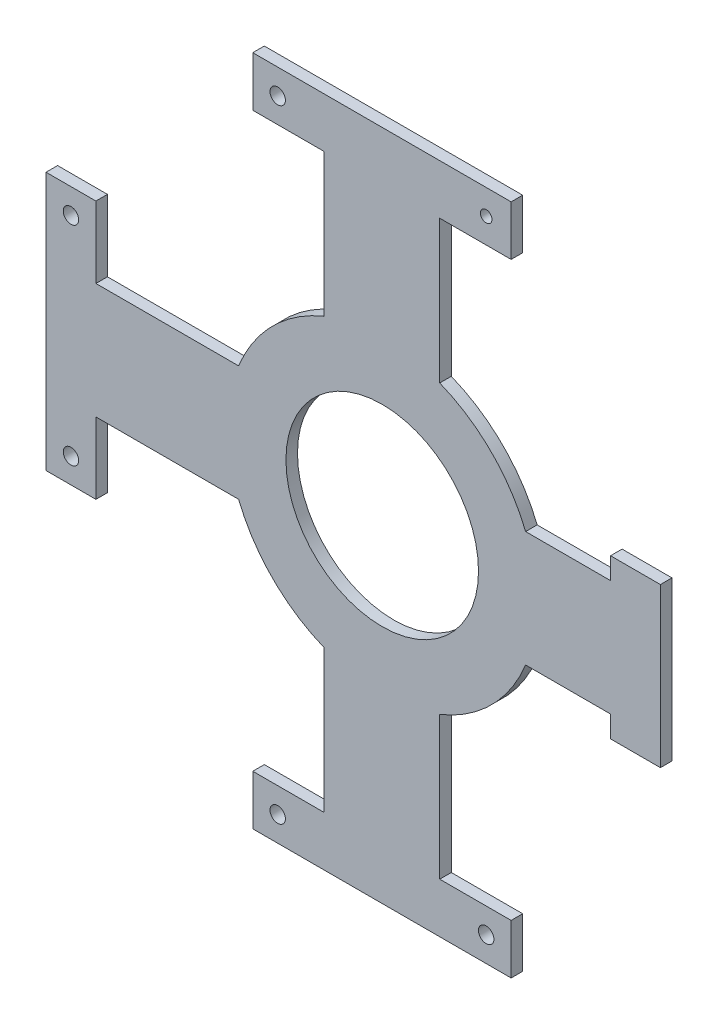
SolidWorks part; units mm, degrees
ref_plane "Alzado" through (0, 0, 0) normal (0, 0, 1) x (1, 0, 0)
ref_plane "Planta" through (0, 0, 0) normal (0, 1, 0) x (1, 0, 0)
ref_plane "Vista lateral" through (0, 0, 0) normal (1, 0, 0) x (0, 0, -1)
sketch "Croquis1" plane through (0, 0, 0) normal (0, 0, 1) x (1, 0, 0)
  line L0 (0, 0) -> (0, 37.2565) construction
  line L1 (-15.071, 74.3065) -> (-15.071, 37.2565)
  line L2 (-37.2851, 15) -> (-74.3351, 15)
  line L3 (-15.071, 37.2565) -> (14.929, 37.2565) construction
  line L4 (14.929, 37.2565) -> (14.929, 74.3065)
  line L5 (-15.071, 74.3065) -> (-20.661, 74.3065)
  line L6 (-25, 0) -> (25, 0) construction
  line L7 (0, 25) -> (0, -25) construction
  line L8 (-15.071, -37.2565) -> (-15.071, -74.3065)
  line L9 (14.929, -37.2565) -> (14.929, -74.3065)
  line L10 (14.929, 74.3065) -> (20.519, 74.3065)
  line L12 (-37.2851, -15) -> (-74.3351, -15)
  line L13 (-20.661, 74.3065) -> (-20.661, 87.2565)
  line L14 (-20.661, 87.2565) -> (20.519, 87.2565)
  line L15 (20.519, 87.2565) -> (20.519, 74.3065)
  line L16 (20.519, -87.2565) -> (20.519, -74.3065)
  line L17 (14.929, -74.3065) -> (20.519, -74.3065)
  line L18 (-20.661, -87.2565) -> (20.519, -87.2565)
  line L19 (-20.661, -74.3065) -> (-20.661, -87.2565)
  line L20 (-15.071, -74.3065) -> (-20.661, -74.3065)
  line L21 (-74.3351, -15) -> (-74.3351, -20.59)
  line L22 (-74.3351, -20.59) -> (-87.2851, -20.59)
  line L23 (-87.2851, -20.59) -> (-87.2851, 20.59)
  line L24 (-87.2851, 20.59) -> (-74.3351, 20.59)
  line L25 (-74.3351, 20.59) -> (-74.3351, 15)
  line L26 (37.228, 15) -> (59.278, 15)
  line L27 (37.228, -15) -> (59.278, -15)
  line L28 (59.278, -15) -> (59.278, -20.59)
  line L29 (59.278, -20.59) -> (72.228, -20.59)
  line L30 (72.228, -20.59) -> (72.228, 20.59)
  line L31 (72.228, 20.59) -> (59.278, 20.59)
  line L32 (59.278, 20.59) -> (59.278, 15)
  arc A0 (-15.071, 37.2565) -> (-37.2851, 15) centre (0, 0) ccw
  circle A1 centre (0, 0) radius 25
  arc A2 (-37.2851, -15) -> (-15.071, -37.2565) centre (0, 0) ccw
  arc A3 (14.929, 37.2565) -> (37.228, 15) centre (0, 0) cw
  arc A4 (14.929, -37.2565) -> (37.228, -15) centre (0, 0) ccw
  dimension "D1" = 50
  dimension "D2" = 5.59
  dimension "D3" = 37.05
  dimension "D4" = 5.59
  dimension "D5" = 12.95
  dimension "D6" = 37.05
  dimension "D7" = 37.05
  dimension "D8" = 5.59
  dimension "D9" = 5.59
  dimension "D10" = 12.95
  dimension "D11" = 37.05
  dimension "D12" = 37.05
  dimension "D13" = 22.05
  dimension "D14" = 5.59
  dimension "D15" = 22.05
  dimension "D16" = 5.59
  dimension "D17" = 12.95
  dimension "D18" = 12.95
  dimension "D19" = 30
  dimension "D20" = 12.95
  dimension "D21" = 41.18
extrude "Saliente-Extruir1" add sketch "Croquis1" along normal blind 3
sketch "Croquis2" plane through (0, 0, 0) normal (0, 0, -1) x (-1, 0, 0)
  line L1 (-20.519, 87.2565) -> (-33.469, 87.2565)
  line L2 (-20.519, 87.2565) -> (-20.519, 74.3065)
  line L3 (-20.519, 74.3065) -> (-33.469, 74.3065)
  line L4 (-33.469, 87.2565) -> (-33.469, 74.3065)
  line L5 (20.661, 87.2565) -> (33.611, 87.2565)
  line L6 (20.661, 87.2565) -> (20.661, 74.3065)
  line L7 (20.661, 74.3065) -> (33.611, 74.3065)
  line L8 (33.611, 87.2565) -> (33.611, 74.3065)
  line L9 (-20.519, -74.3065) -> (-33.469, -74.3065)
  line L10 (-20.519, -74.3065) -> (-20.519, -87.2565)
  line L11 (-20.519, -87.2565) -> (-33.469, -87.2565)
  line L12 (-33.469, -74.3065) -> (-33.469, -87.2565)
  line L13 (20.661, -74.3065) -> (33.611, -74.3065)
  line L14 (20.661, -74.3065) -> (20.661, -87.2565)
  line L15 (20.661, -87.2565) -> (33.611, -87.2565)
  line L16 (33.611, -74.3065) -> (33.611, -87.2565)
  line L17 (74.3351, 20.59) -> (87.2851, 20.59)
  line L18 (74.3351, 20.59) -> (74.3351, 33.54)
  line L19 (74.3351, 33.54) -> (87.2851, 33.54)
  line L20 (87.2851, 20.59) -> (87.2851, 33.54)
  line L21 (74.3351, -20.59) -> (87.2851, -20.59)
  line L22 (74.3351, -20.59) -> (74.3351, -33.54)
  line L23 (74.3351, -33.54) -> (87.2851, -33.54)
  line L24 (87.2851, -20.59) -> (87.2851, -33.54)
  dimension "D1" = 12.95
  dimension "D2" = 12.95
  dimension "D3" = 12.95
  dimension "D4" = 12.95
  dimension "D5" = 12.95
  dimension "D6" = 12.95
  dimension "D7" = 12.95
  dimension "D8" = 12.95
  dimension "D9" = 12.95
  dimension "D10" = 12.95
  dimension "D11" = 12.95
extrude "Saliente-Extruir2" add sketch "Croquis2" against normal blind 3
sketch "Croquis3" plane through (0, 0, 0) normal (0, 0, -1) x (-1, 0, 0)
  line L0 (-33.469, 74.3065) -> (-20.519, 74.3065) construction
  line L1 (-14.929, 74.3065) -> (-33.469, 74.3065) construction
  line L2 (-33.469, 74.3065) -> (-20.519, 87.2565) construction
  line L3 (33.611, 87.2565) -> (-33.469, 87.2565) construction
  line L4 (-20.519, -74.3065) -> (-20.519, -87.2565) construction
  line L5 (-14.929, -74.3065) -> (-33.469, -74.3065) construction
  line L6 (33.611, -87.2565) -> (-33.469, -87.2565) construction
  line L7 (33.611, 87.2565) -> (20.661, 87.2565) construction
  line L8 (20.661, 87.2565) -> (20.661, 74.3065) construction
  line L9 (15.071, 74.3065) -> (33.611, 74.3065) construction
  line L10 (33.611, -74.3065) -> (20.661, -74.3065) construction
  line L12 (-33.469, -74.3065) -> (-20.519, -87.2565) construction
  line L13 (15.071, -74.3065) -> (33.611, -74.3065) construction
  line L14 (20.661, 74.3065) -> (33.611, 74.3065) construction
  line L15 (33.611, 74.3065) -> (20.661, 87.2565) construction
  line L16 (87.2851, -33.54) -> (87.2851, -20.59) construction
  line L17 (87.2851, -33.54) -> (87.2851, 33.54) construction
  line L18 (87.2851, -20.59) -> (74.3351, -20.59) construction
  line L19 (74.3351, -15) -> (74.3351, -33.54) construction
  line L20 (87.2851, 33.54) -> (87.2851, 20.59) construction
  line L21 (87.2851, 20.59) -> (74.3351, 20.59) construction
  line L22 (74.3351, 33.54) -> (74.3351, 15) construction
  line L23 (87.2851, 20.59) -> (74.3351, 33.54) construction
  line L24 (74.3351, -33.54) -> (87.2851, -20.59) construction
  line L26 (-20.519, -74.3065) -> (-33.469, -74.3065) construction
  line L27 (-33.469, 87.2565) -> (-33.469, 74.3065) construction
  line L28 (33.611, 74.3065) -> (33.611, 87.2565) construction
  line L29 (87.2851, 33.54) -> (74.3351, 33.54) construction
  line L30 (74.3351, -33.54) -> (87.2851, -33.54) construction
  line L32 (-33.469, -74.3065) -> (-33.469, -87.2565) construction
  line L33 (20.661, -74.3065) -> (20.661, -87.2565) construction
  line L34 (20.661, -87.2565) -> (33.611, -74.3065) construction
  line L35 (33.611, -87.2565) -> (33.611, -74.3065) construction
  circle A0 centre (-26.994, 80.7815) radius 1.5
  circle A1 centre (27.136, 80.7815) radius 2
  circle A2 centre (27.136, -80.7815) radius 2
  circle A3 centre (-26.994, -80.7815) radius 2
  circle A4 centre (80.8101, -27.065) radius 2
  circle A5 centre (80.8101, 27.065) radius 2
  dimension "D1" = 4
  dimension "D2" = 4
  dimension "D3" = 4
  dimension "D4" = 4
  dimension "D5" = 3
  dimension "D6" = 4
  dimension "D7" = 6.475
  dimension "D8" = 6.475
  dimension "D9" = 6.475
  dimension "D10" = 6.475
  dimension "D11" = 6.475
  dimension "D12" = 6.475
extrude "Cortar-Extruir1" cut sketch "Croquis3" against normal through all
